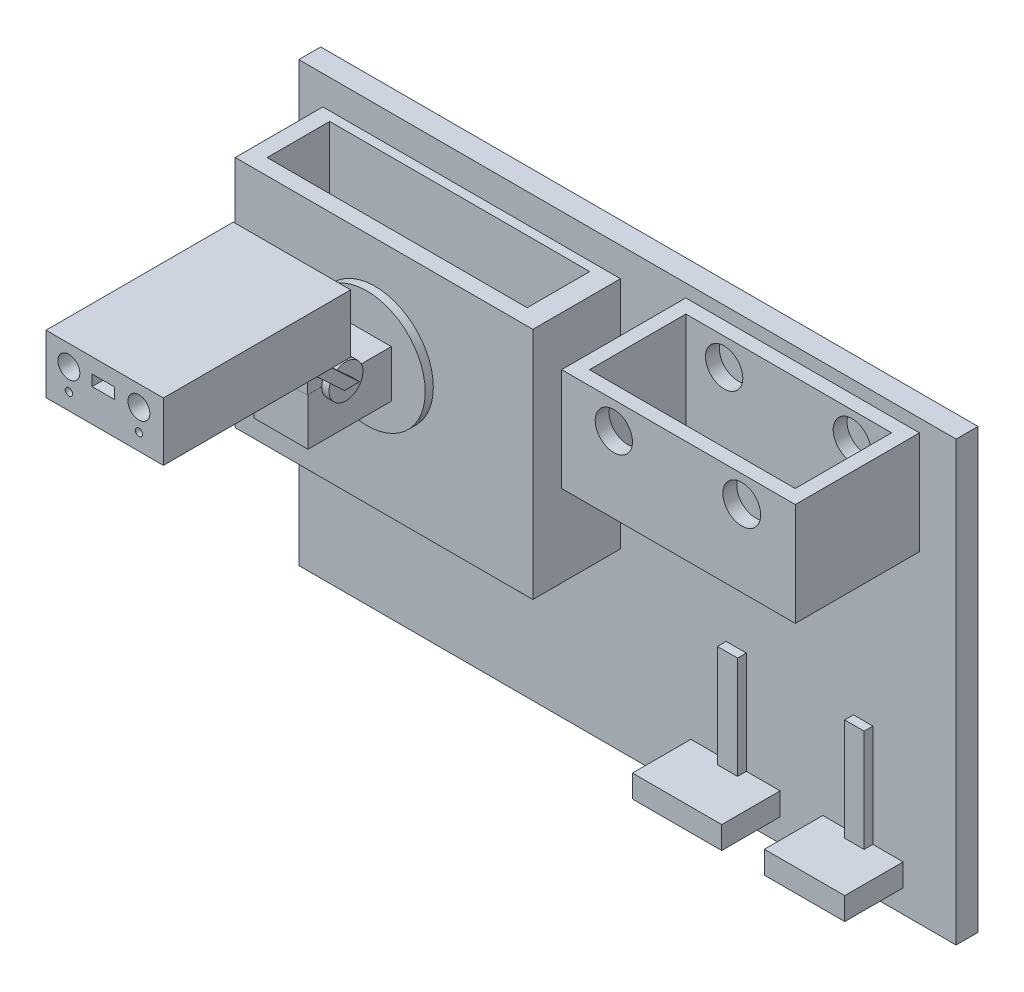
SolidWorks part; units mm, degrees
ref_plane "Front Plane" through (0, 0, 0) normal (0, 0, 1) x (1, 0, 0)
ref_plane "Top Plane" through (0, 0, 0) normal (0, 1, 0) x (1, 0, 0)
ref_plane "Right Plane" through (0, 0, 0) normal (1, 0, 0) x (0, 0, -1)
sketch "Sketch2" plane through (0, 0, 0) normal (0, 0, 1) x (1, 0, 0)
  line L1 (225, -150) -> (-225, -150)
  line L2 (225, -150) -> (225, 150)
  line L3 (225, 150) -> (-225, 150)
  line L4 (-225, -150) -> (-225, 150)
  line L5 (225, -150) -> (-225, 150) construction
  line L6 (225, 150) -> (-225, -150) construction
  point P0 (0, 0)
  dimension "D1" = 450
  dimension "D2" = 300
extrude "Boss-Extrude1" add sketch "Sketch2" against normal blind 15
sketch "Sketch3" plane through (0, 0, 0) normal (0, 0, 1) x (1, 0, 0)
  line L0 (0, 150) -> (0, -150)
  line L1 (225, 150) -> (-225, 150) construction
  line L2 (-225, -150) -> (225, -150) construction
  line L3 (-225, 0) -> (225, 0)
  line L4 (-225, 150) -> (-225, -150) construction
  line L5 (225, -150) -> (225, 150) construction
  line L7 (199.9375, 70.6922) -> (39.9375, 70.6922)
  line L8 (199.9375, 70.6922) -> (199.9375, 141.1464)
  line L9 (199.9375, 141.1464) -> (39.9375, 141.1464)
  line L10 (39.9375, 70.6922) -> (39.9375, 141.1464)
  line L11 (199.9375, 70.6922) -> (39.9375, 141.1464) construction
  line L12 (199.9375, 141.1464) -> (39.9375, 70.6922) construction
  point P12 (119.9375, 105.9193)
  dimension "D1" = 160
  dimension "D2" = 70.4542
extrude "Boss-Extrude2" add sketch "Sketch3" along normal blind 85 contours L8 L7 L10 L9
sketch "Sketch4" plane through (0, 141.1464, 0) normal (0, 1, 0) x (1, 0, 0)
  line L7 (190.3667, -75.5072) -> (49.5083, -75.5072)
  line L8 (190.3667, -75.5072) -> (190.3667, -9.4928)
  line L9 (190.3667, -9.4928) -> (49.5083, -9.4928)
  line L10 (49.5083, -75.5072) -> (49.5083, -9.4928)
  point P6 (0, 0)
  point P12 (119.9375, -42.5)
  point P17 (0, 0)
extrude "Cut-Extrude1" cut sketch "Sketch4" against normal blind 85 contours L8 L7 L10 L9
sketch "Sketch5" plane through (0, 0, 0) normal (0, 0, 1) x (1, 0, 0)
  line L0 (0, 150) -> (0, -150) construction
  line L1 (225, 150) -> (-225, 150) construction
  line L2 (-225, -150) -> (225, -150) construction
  line L3 (-225, 0) -> (225, 0) construction
  line L4 (-225, 150) -> (-225, -150) construction
  line L5 (225, -150) -> (225, 150) construction
sketch "Sketch6" plane through (0, 0, 0) normal (0, 0, 1) x (1, 0, 0)
  line L1 (-4.7604, -24.9922) -> (-208.5063, -24.9922)
  line L2 (-4.7604, -24.9922) -> (-4.7604, 130.1974)
  line L3 (-4.7604, 130.1974) -> (-208.5063, 130.1974)
  line L4 (-208.5063, -24.9922) -> (-208.5063, 130.1974)
  line L5 (-4.7604, -24.9922) -> (-208.5063, 130.1974) construction
  line L6 (-4.7604, 130.1974) -> (-208.5063, -24.9922) construction
  point P0 (-106.6333, 52.6026)
  dimension "D1" = 203.7459
  dimension "D2" = 155.1896
extrude "Boss-Extrude3" add sketch "Sketch6" along normal blind 60
sketch "Sketch7" plane through (0, 130.1974, 0) normal (0, 1, 0) x (1, 0, 0)
  line L1 (-19.5177, -49.1287) -> (-197.5573, -49.1287)
  line L2 (-19.5177, -49.1287) -> (-19.5177, -6.285)
  line L3 (-19.5177, -6.285) -> (-197.5573, -6.285)
  line L4 (-197.5573, -49.1287) -> (-197.5573, -6.285)
  line L5 (-19.5177, -49.1287) -> (-197.5573, -6.285) construction
  line L6 (-19.5177, -6.285) -> (-197.5573, -49.1287) construction
  point P0 (-108.5375, -27.7068)
extrude "Cut-Extrude2" cut sketch "Sketch7" against normal through all
sketch "Sketch8" plane through (0, 0, 85) normal (0, 0, 1) x (1, 0, 0)
  line L0 (39.9375, 105.9193) -> (199.9375, 105.9193)
  line L1 (39.9375, 70.6922) -> (39.9375, 141.1464) construction
  line L2 (199.9375, 70.6922) -> (199.9375, 141.1464) construction
  line L4 (199.9375, 141.1464) -> (39.9375, 141.1464) construction
  line L5 (119.9375, 141.1464) -> (119.9375, 70.6922)
  line L6 (199.9375, 70.6922) -> (39.9375, 70.6922) construction
sketch "Sketch9" plane through (0, 0, 0) normal (0, 0, 1) x (1, 0, 0)
  circle A0 centre (75.6906, 122.5807) radius 12.7735
extrude "Cut-Extrude3" cut sketch "Sketch9" along normal through all
sketch "Sketch10" plane through (0, 0, 0) normal (0, 0, 1) x (1, 0, 0)
  circle A0 centre (163.2823, 123.0568) radius 12.9497
extrude "Cut-Extrude4" cut sketch "Sketch10" along normal through all
sketch "Sketch11" plane through (0, -24.9922, 0) normal (0, -1, 0) x (1, 0, 0)
  line L1 (-208.5063, 60) -> (-4.7604, 60)
  line L2 (-208.5063, 60) -> (-208.5063, 0)
  line L3 (-208.5063, 0) -> (-4.7604, 0)
  line L4 (-4.7604, 60) -> (-4.7604, 0)
extrude "Boss-Extrude4" add sketch "Sketch11" along normal blind 5
sketch "Sketch12" plane through (0, 0, 0) normal (0, 0, 1) x (1, 0, 0)
  line L0 (39.9375, 70.6922) -> (39.9375, -153.5235) construction
  line L1 (119.9375, 70.6922) -> (119.9375, -153.5235) construction
  line L2 (199.9375, 70.6922) -> (199.9375, -150) construction
  line L3 (-225, -150) -> (225, -150) construction
sketch "Sketch13" plane through (0, 0, 0) normal (0, 0, 1) x (1, 0, 0)
  line L0 (62.9171, 122.5807) -> (62.9171, -150) construction
  line L1 (-225, -150) -> (225, -150) construction
  line L2 (88.4642, 122.5807) -> (88.4642, -150) construction
  line L3 (150.3326, 123.0568) -> (150.3326, -150) construction
  line L4 (176.232, 123.0568) -> (176.232, -150)
  circle A0 centre (75.6906, 122.5807) radius 12.7735 construction
  circle A1 centre (75.6906, 122.5807) radius 12.7735 construction
  circle A2 centre (163.2823, 123.0568) radius 12.9497 construction
  circle A3 centre (163.2823, 123.0568) radius 12.9497 construction
sketch "Sketch14" plane through (0, 0, 0) normal (0, 0, 1) x (1, 0, 0)
  line L0 (52.8406, 70.6922) -> (52.8406, -150) construction
  line L1 (199.9375, 70.6922) -> (39.9375, 70.6922) construction
  line L2 (-225, -150) -> (225, -150) construction
  line L3 (96.6365, 70.6922) -> (96.6365, -150) construction
  line L4 (199.9375, 70.6922) -> (39.9375, 70.6922) construction
  line L5 (140.4323, 70.6922) -> (140.4323, -150) construction
  line L6 (184.2281, 70.6922) -> (184.2281, -150) construction
  line L8 (67.5979, -48.6518) -> (81.4031, -48.6518)
  line L9 (67.5979, -48.6518) -> (67.5979, -119.106)
  line L10 (67.5979, -119.106) -> (81.4031, -119.106)
  line L11 (81.4031, -48.6518) -> (81.4031, -119.106)
  line L12 (154.7136, -48.6518) -> (168.0427, -48.6518)
  line L13 (154.7136, -48.6518) -> (154.7136, -119.106)
  line L14 (154.7136, -119.106) -> (168.0427, -119.106)
  line L15 (168.0427, -48.6518) -> (168.0427, -119.106)
extrude "Boss-Extrude7" add sketch "Sketch14" along normal blind 6 contours L11 L8 L9 L10 | L15 L12 L13 L14
sketch "Sketch15" plane through (0, 0, 0) normal (0, 0, 1) x (1, 0, 0)
  line L1 (43.4213, -134.2124) -> (104.5384, -134.2124)
  line L2 (43.4213, -134.2124) -> (43.4213, -118.8003)
  line L3 (43.4213, -118.8003) -> (104.5384, -118.8003)
  line L4 (104.5384, -134.2124) -> (104.5384, -118.8003)
  line L5 (133.7684, -134.2124) -> (188.7738, -134.2124)
  line L6 (133.7684, -134.2124) -> (133.7684, -118.8003)
  line L7 (133.7684, -118.8003) -> (188.7738, -118.8003)
  line L8 (188.7738, -134.2124) -> (188.7738, -118.8003)
extrude "Boss-Extrude8" add sketch "Sketch15" along normal blind 40 contours L5 L8 L7 L6 | L1 L4 L3 L2
ref_plane "Plane1" through (0, 0, 62.54) normal (0, 0, 1) x (1, 0, 0)
sketch "Sketch17" plane through (0, 0, 62.54) normal (0, 0, 1) x (1, 0, 0)
  circle A0 centre (-112.8219, 61.7898) radius 39.9223
extrude "Boss-Extrude9" add sketch "Sketch17" along normal blind 3 and the other way blind 7.366 separate body
sketch "Sketch18" plane through (0, 0, 62.54) normal (0, 0, 1) x (1, 0, 0)
  line L1 (-96.1604, 44.6523) -> (-133.2917, 44.6523)
  line L2 (-96.1604, 44.6523) -> (-96.1604, 77.0232)
  line L3 (-96.1604, 77.0232) -> (-133.2917, 77.0232)
  line L4 (-133.2917, 44.6523) -> (-133.2917, 77.0232)
  line L5 (-96.1604, 44.6523) -> (-133.2917, 77.0232) construction
  line L6 (-96.1604, 77.0232) -> (-133.2917, 44.6523) construction
  point P0 (-114.7261, 60.8378)
extrude "Boss-Extrude10" add sketch "Sketch18" along normal blind 60
ref_plane "Plane2" through (0, 0, 123) normal (0, 0, 1) x (1, 0, 0)
ref_plane "Plane3" through (0, 77.0232, 0) normal (0, 1, 0) x (1, 0, 0)
sketch "Sketch22" plane through (0, 77.0232, 0) normal (0, 1, 0) x (1, 0, 0)
  line L0 (-133.2917, -122.54) -> (-133.2917, -65.54) construction
  line L1 (-133.2917, -101.3974) -> (-96.1957, -101.3974)
  line L2 (-133.2917, -101.3974) -> (-133.2917, -123)
  line L3 (-133.2917, -123) -> (-96.1957, -123)
  line L4 (-96.1957, -101.3974) -> (-96.1957, -123)
  line L5 (-88.1043, -123) -> (88.1043, -123) construction
extrude "Boss-Extrude11" add sketch "Sketch22" along normal blind 10
ref_plane "Plane4" through (0, 87.0232, 0) normal (0, 1, 0) x (1, 0, 0)
ref_plane "Plane5" through (-133.2917, 0, 0) normal (-1, 0, 0) x (0, 0, 1)
sketch "Sketch23" plane through (-133.2917, 0, 0) normal (-1, 0, 0) x (0, 0, 1)
  line L0 (20.4222, 77.0232) -> (-20.4222, 77.0232) construction
  circle A0 centre (101.3495, 77.0232) radius 11.43
  dimension "D1" = 22.86
extrude "Boss-Extrude12" add sketch "Sketch23" along normal blind 5
ref_plane "Plane6" through (-96.1604, 0, 0) normal (1, 0, 0) x (0, 0, -1)
sketch "Sketch24" plane through (-96.1604, 0, 0) normal (1, 0, 0) x (0, 0, -1)
  line L0 (20.4222, 77.0232) -> (-20.4222, 77.0232) construction
  circle A0 centre (-101.5288, 77.0232) radius 11.6093
extrude "Boss-Extrude13" add sketch "Sketch24" along normal blind 5
ref_plane "Plane8" through (-91.1604, 0, 0) normal (1, 0, 0) x (0, 0, -1)
sketch "Sketch25" plane through (-91.1604, 0, 0) normal (1, 0, 0) x (0, 0, -1)
  line L0 (-97.1881, 77.0232) -> (-107.529, 77.0232)
  line L1 (-97.1881, 77.0232) -> (-129.6084, 107.0549)
  line L2 (-107.529, 77.0232) -> (-139.9493, 107.0549)
  line L3 (-129.6084, 107.0549) -> (-139.9493, 107.0549)
  line L4 (20.4222, 77.0232) -> (-20.4222, 77.0232) construction
extrude "Boss-Extrude14" add sketch "Sketch25" along normal blind 5
ref_plane "Plane9" through (-138.2917, 0, 0) normal (-1, 0, 0) x (0, 0, 1)
sketch "Sketch26" plane through (-138.2917, 0, 0) normal (-1, 0, 0) x (0, 0, 1)
  line L0 (129.6084, 107.0549) -> (139.9493, 107.0549)
  line L1 (129.6084, 107.0549) -> (97.063, 77.0232)
  line L2 (139.9493, 107.0549) -> (107.4039, 77.0232)
  line L3 (97.063, 77.0232) -> (107.4039, 77.0232)
  line L4 (20.4222, 77.0232) -> (-20.4222, 77.0232) construction
extrude "Boss-Extrude15" add sketch "Sketch26" along normal blind 5
ref_plane "Plane10" through (0, 107.0549, 0) normal (0, 1, 0) x (1, 0, 0)
sketch "Sketch30" plane through (0, 107.0549, 0) normal (0, 1, 0) x (1, 0, 0)
  line L1 (-154.0306, -244.0369) -> (-73.6702, -244.0369)
  line L2 (-154.0306, -244.0369) -> (-154.0306, -115.8191)
  line L3 (-154.0306, -115.8191) -> (-73.6702, -115.8191)
  line L4 (-73.6702, -244.0369) -> (-73.6702, -115.8191)
  point P4 (-154.0306, -244.0369)
extrude "Boss-Extrude17" add sketch "Sketch30" along normal blind 40
ref_plane "Plane12" through (0, 0, 244.0369) normal (0, 0, 1) x (1, 0, 0)
sketch "Sketch35" plane through (0, 0, 244.0369) normal (0, 0, 1) x (1, 0, 0)
  line L1 (-149.2274, 143.1594) -> (-78.0498, 143.1594)
  line L2 (-149.2274, 143.1594) -> (-149.2274, 111.5106)
  line L3 (-149.2274, 111.5106) -> (-78.0498, 111.5106)
  line L4 (-78.0498, 143.1594) -> (-78.0498, 111.5106)
extrude "Cut-Extrude6" cut sketch "Sketch35" against normal blind 119.408
sketch "Sketch38" plane through (0, 0, 244.0369) normal (0, 0, 1) x (1, 0, 0)
  line L1 (-107.2513, 129.4013) -> (-122.5037, 129.4013)
  line L2 (-107.2513, 129.4013) -> (-107.2513, 136.8719)
  line L3 (-107.2513, 136.8719) -> (-122.5037, 136.8719)
  line L4 (-122.5037, 129.4013) -> (-122.5037, 136.8719)
  line L5 (-107.2513, 129.4013) -> (-122.5037, 136.8719) construction
  line L6 (-107.2513, 136.8719) -> (-122.5037, 129.4013) construction
  circle A0 centre (-138.3787, 133.1366) radius 7.5
  circle A1 centre (-138.3787, 118.351) radius 2.5
  circle A2 centre (-90.4424, 133.1366) radius 7.5
  circle A3 centre (-90.4424, 118.351) radius 2.5
  point P8 (-114.8775, 133.1366)
  dimension "D1" = 15
  dimension "D2" = 5
  dimension "D3" = 15
  dimension "D4" = 5
sketch "Sketch39" plane through (0, 0, 244.0369) normal (0, 0, 1) x (1, 0, 0)
  line L0 (-73.6702, 147.0549) -> (-73.6702, 107.0549) construction
  line L1 (-154.0306, 147.0549) -> (-73.6702, 147.0549)
  line L2 (-154.0306, 147.0549) -> (-154.0306, 107.0549)
  line L3 (-154.0306, 107.0549) -> (-73.6702, 107.0549)
  line L4 (-73.6702, 147.0549) -> (-73.6702, 107.0549)
  line L5 (-154.0306, 107.0549) -> (-73.6702, 107.0549) construction
extrude "Boss-Extrude19" add sketch "Sketch39" against normal blind 15
extrude "Cut-Extrude7" cut sketch "Sketch38" against normal blind 20
